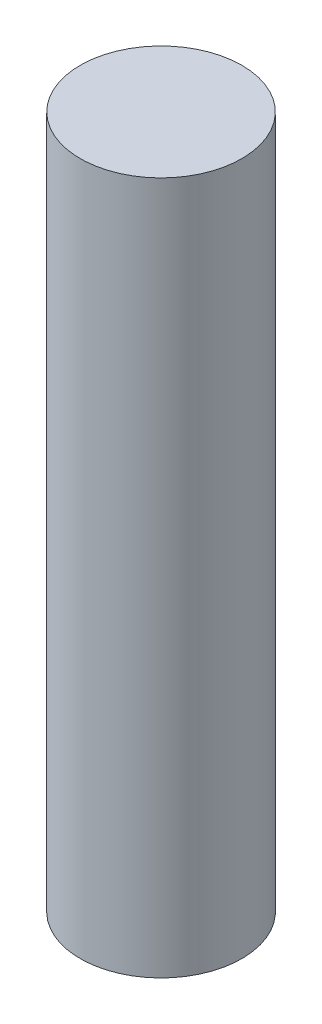
SolidWorks part; units mm, degrees
ref_plane "Front Plane" through (0, 0, 0) normal (0, 0, 1) x (1, 0, 0)
ref_plane "Top Plane" through (0, 0, 0) normal (0, 1, 0) x (1, 0, 0)
ref_plane "Right Plane" through (0, 0, 0) normal (1, 0, 0) x (0, 0, -1)
sketch "Sketch1" plane through (0, 0, 0) normal (0, 1, 0) x (1, 0, 0)
  circle A0 centre (0, 0) radius 2.2225
  dimension "D1" = 4.445
extrude "Boss-Extrude1" add sketch "Sketch1" along normal blind 19.05
